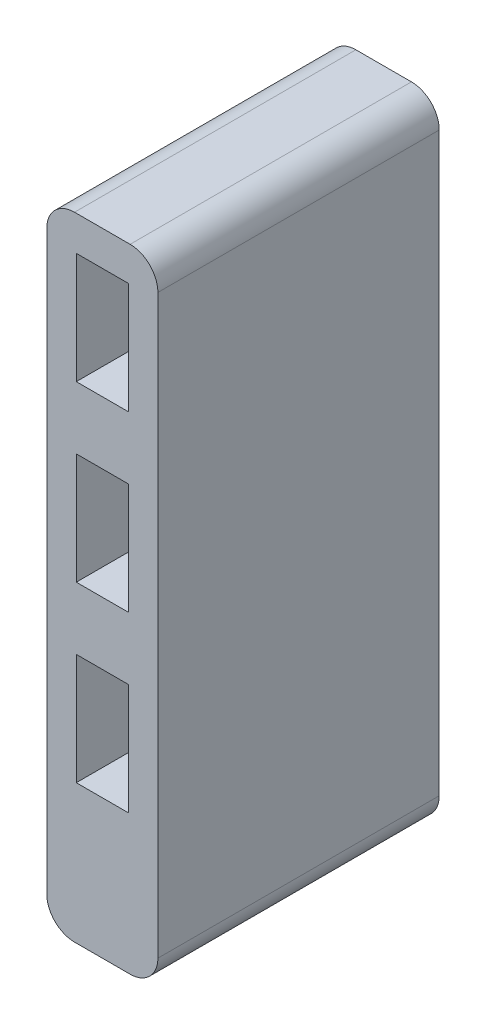
SolidWorks part; units mm, degrees
ref_plane "Front Plane" through (0, 0, 0) normal (0, 0, 1) x (1, 0, 0)
ref_plane "Top Plane" through (0, 0, 0) normal (0, 1, 0) x (1, 0, 0)
ref_plane "Right Plane" through (0, 0, 0) normal (1, 0, 0) x (0, 0, -1)
sketch "Sketch1" plane through (0, 0, 0) normal (0, 0, 1) x (1, 0, 0)
  line L1 (-4, -45.5) -> (4, -45.5)
  line L2 (-8, -41.5) -> (-8, 41.5)
  line L3 (-4, 45.5) -> (4, 45.5)
  line L4 (8, -41.5) -> (8, 41.5)
  line L5 (-8, -45.5) -> (8, 45.5) construction
  line L6 (-8, 45.5) -> (8, -45.5) construction
  arc A0 (-4, -45.5) -> (-8, -41.5) centre (-4, -41.5) cw
  arc A1 (4, -45.5) -> (8, -41.5) centre (4, -41.5) ccw
  arc A2 (8, 41.5) -> (4, 45.5) centre (4, 41.5) ccw
  arc A3 (-8, 41.5) -> (-4, 45.5) centre (-4, 41.5) cw
  point P0 (0, 0)
  dimension "D3" = 4
  dimension "D1" = 91
  dimension "D2" = 16
extrude "Boss-Extrude1" add sketch "Sketch1" along normal blind 40.5
sketch "Sketch2" plane through (0, 0, 40.5) normal (0, 0, 1) x (1, 0, 0)
  line L0 (0, 45.5) -> (0, -45.5) construction
  line L1 (4, 45.5) -> (-4, 45.5) construction
  line L2 (-4, -45.5) -> (4, -45.5) construction
  line L3 (-3.75, -0.5) -> (3.75, -0.5)
  line L4 (-3.75, 40.5) -> (3.75, 40.5)
  line L5 (-3.75, 40.5) -> (-3.75, 24.5)
  line L6 (-3.75, 24.5) -> (3.75, 24.5)
  line L7 (3.75, 40.5) -> (3.75, 24.5)
  line L8 (-3.75, 40.5) -> (3.75, 24.5) construction
  line L9 (-3.75, 24.5) -> (3.75, 40.5) construction
  line L10 (3.75, 15.5) -> (3.75, -0.5)
  line L11 (-3.75, 15.5) -> (-3.75, -0.5)
  line L12 (-3.75, 15.5) -> (3.75, 15.5)
  line L13 (-3.75, -25.5) -> (3.75, -25.5)
  line L14 (3.75, -9.5) -> (3.75, -25.5)
  line L15 (-3.75, -9.5) -> (-3.75, -25.5)
  line L16 (-3.75, -9.5) -> (3.75, -9.5)
  point P6 (0, 32.5)
  dimension "D1" = 7.5
  dimension "D2" = 16
  dimension "D3" = 5
  dimension "D4" = 3
extrude "Cut-Extrude1" cut sketch "Sketch2" against normal blind 12.5
